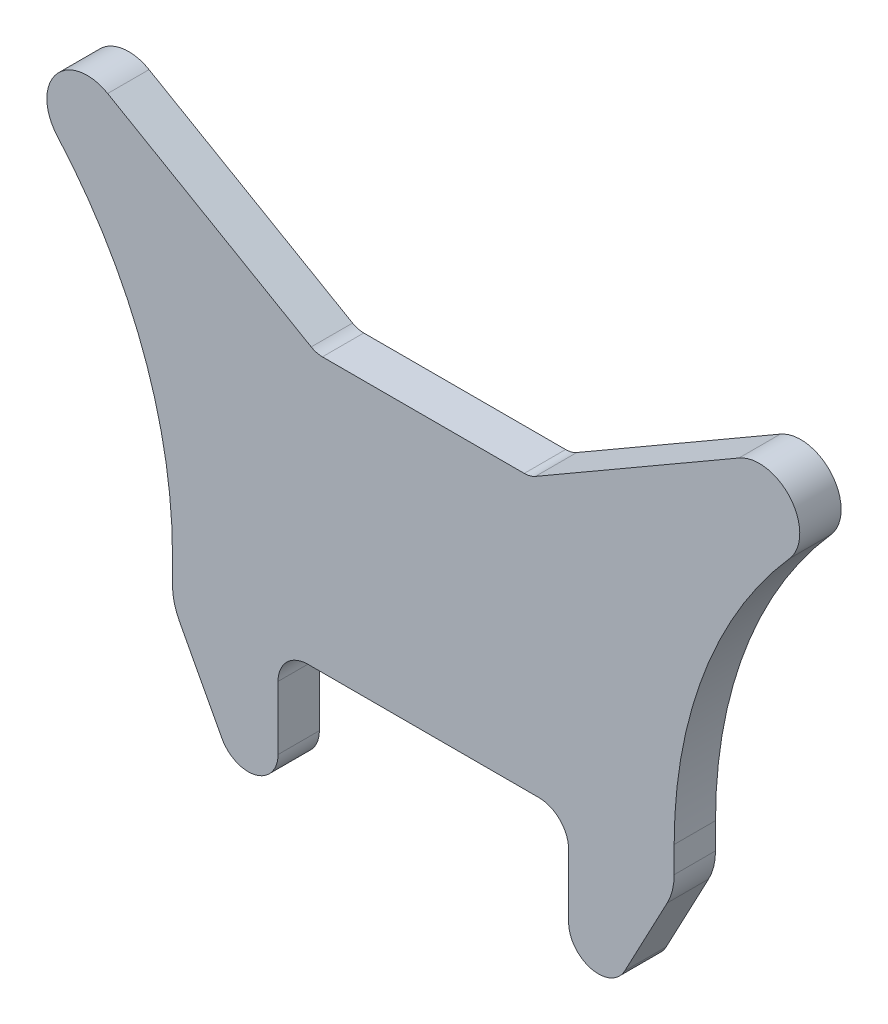
SolidWorks part; units mm, degrees
material "Náilon 6/10"
ref_plane "Plano frontal" through (0, 0, 0) normal (0, 0, 1) x (1, 0, 0)
ref_plane "Plano superior" through (0, 0, 0) normal (0, 1, 0) x (1, 0, 0)
ref_plane "Plano direito" through (0, 0, 0) normal (1, 0, 0) x (0, 0, -1)
sketch "Esboço1" plane through (0, 0, 0) normal (0, 0, 1) x (1, 0, 0)
  line L0 (0, 45.9239) -> (0, -39.7065) construction
  line L1 (-15.5, -28.1196) -> (15.5, -28.1196)
  line L2 (19.5, -32.1196) -> (19.5, -40.6196)
  line L3 (27.0336, -42.4941) -> (32.7319, -31.7526)
  line L4 (33.6647, -28.0035) -> (33.6647, -24.4941)
  line L5 (42.3624, 24.7804) -> (15.0469, 8.9834)
  line L6 (13.545, 8.5804) -> (-13.545, 8.5804)
  line L7 (-42.3624, 24.7804) -> (-15.0469, 8.9834)
  line L8 (-33.6647, -28.0035) -> (-33.6647, -24.4941)
  line L9 (-27.0336, -42.4941) -> (-32.7319, -31.7526)
  line L10 (-19.5, -32.1196) -> (-19.5, -40.6196)
  arc A0 (19.5, -40.6196) -> (27.0336, -42.4941) centre (23.5, -40.6196) ccw
  arc A1 (33.6647, -24.4941) -> (49.1647, 16.5059) centre (95.6406, -24.4941) cw
  arc A2 (49.1647, 16.5059) -> (42.3624, 24.7804) centre (45.0965, 20.0948) ccw
  arc A3 (33.6647, -28.0035) -> (32.7319, -31.7526) centre (25.6647, -28.0035) cw
  arc A4 (19.5, -32.1196) -> (15.5, -28.1196) centre (15.5, -32.1196) ccw
  arc A5 (15.0469, 8.9834) -> (13.545, 8.5804) centre (13.545, 11.5804) cw
  arc A6 (-15.0469, 8.9834) -> (-13.545, 8.5804) centre (-13.545, 11.5804) ccw
  arc A7 (-19.5, -32.1196) -> (-15.5, -28.1196) centre (-15.5, -32.1196) cw
  arc A8 (-33.6647, -28.0035) -> (-32.7319, -31.7526) centre (-25.6647, -28.0035) ccw
  arc A9 (-49.1647, 16.5059) -> (-42.3624, 24.7804) centre (-45.0965, 20.0948) cw
  arc A10 (-33.6647, -24.4941) -> (-49.1647, 16.5059) centre (-95.6406, -24.4941) ccw
  arc A11 (-19.5, -40.6196) -> (-27.0336, -42.4941) centre (-23.5, -40.6196) cw
  point P1 (-14.35, 8.5804)
  point P16 (0, -28.1196)
  point P18 (33.6647, -29.9941)
  point P21 (19.5, -28.1196)
  point P24 (14.35, 8.5804)
  point P42 (0, 8.5804)
  point P43 (-19.5, -28.1196)
  point P44 (-33.6647, -29.9941)
  dimension "D3" = 4
  dimension "D8" = 5.425
  dimension "D14" = 8
  dimension "D15" = 4
  dimension "D16" = 3
  dimension "D1" = 19.5
  dimension "D2" = 12.5
  dimension "D4" = 14.15
  dimension "D5" = 12.5
  dimension "D6" = 5.5
  dimension "D7" = 41
  dimension "D9" = 14.35
  dimension "D10" = 36.7
  dimension "D11" = 28.1196
  dimension "D12" = 15.5
  dimension "D13" = 16.2
extrude "Ressalto-extrusão1" add sketch "Esboço1" along normal blind 5.55
